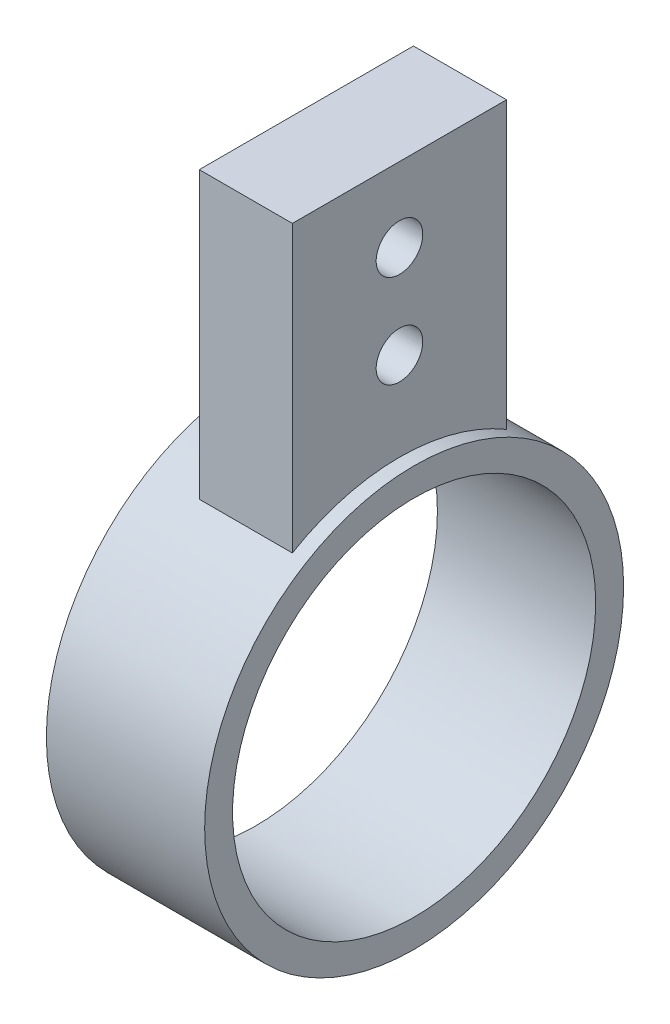
SolidWorks part; units mm, degrees
other "Markup1"
sketch "Sketch7" plane through (9, 62, 20) normal (0.871, 0.218, 0.4404) x (0.4765, -0.1561, -0.8652)
material "1060 Alloy"
ref_plane "Front Plane" through (0, 0, 0) normal (0, 0, 1) x (1, 0, 0)
ref_plane "Top Plane" through (0, 0, 0) normal (0, 1, 0) x (1, 0, 0)
ref_plane "Right Plane" through (0, 0, 0) normal (1, 0, 0) x (0, 0, -1)
sketch "Sketch2" plane through (0, 0, 0) normal (1, 0, 0) x (0, 0, -1)
  circle A0 centre (0, 0) radius 22.5
  dimension "24" = 45
extrude "Boss-Extrude1" add sketch "Sketch2" along normal mid plane 17
ref_point "Point1"
ref_plane "Plane2" through (0, 50, 0) normal (0, 1, 0) x (1, 0, 0)
sketch "Sketch3" plane through (0, 50, 0) normal (0, 1, 0) x (1, 0, 0)
  line L1 (-3.0768, 11.5) -> (6.9232, 11.5)
  line L2 (-3.0768, 11.5) -> (-3.0768, -11.5)
  line L3 (-3.0768, -11.5) -> (6.9232, -11.5)
  line L4 (6.9232, 11.5) -> (6.9232, -11.5)
  line L5 (-3.0768, 11.5) -> (6.9232, -11.5) construction
  line L6 (-3.0768, -11.5) -> (6.9232, 11.5) construction
  point P0 (1.9232, 0)
  dimension "D1" = 10
  dimension "D2" = 23
extrude "Boss-Extrude2" add sketch "Sketch3" against normal up to next
sketch "Sketch8" plane through (6.9232, 0, 0) normal (1, 0, 0) x (0, 0, -1)
  line L0 (-11.5, 19.3391) -> (-11.5, 50) construction
  line L1 (9.35, 50) -> (-9.35, 50) construction
  circle A0 centre (0, 42) radius 2.5
  circle A1 centre (0, 32) radius 2.5
  dimension "D1" = 5
  dimension "D2" = 5
  dimension "D3" = 11.5
  dimension "D4" = 11.5
  dimension "D5" = 8
  dimension "D6" = 10
extrude "Cut-Extrude1" cut sketch "Sketch8" against normal through all
sketch "Sketch11" plane through (8.5, 0, 0) normal (1, 0, 0) x (0, 0, -1)
  circle A0 centre (0, 0) radius 19.5
  dimension "D1" = 39
extrude "Cut-Extrude2" cut sketch "Sketch11" against normal through all
